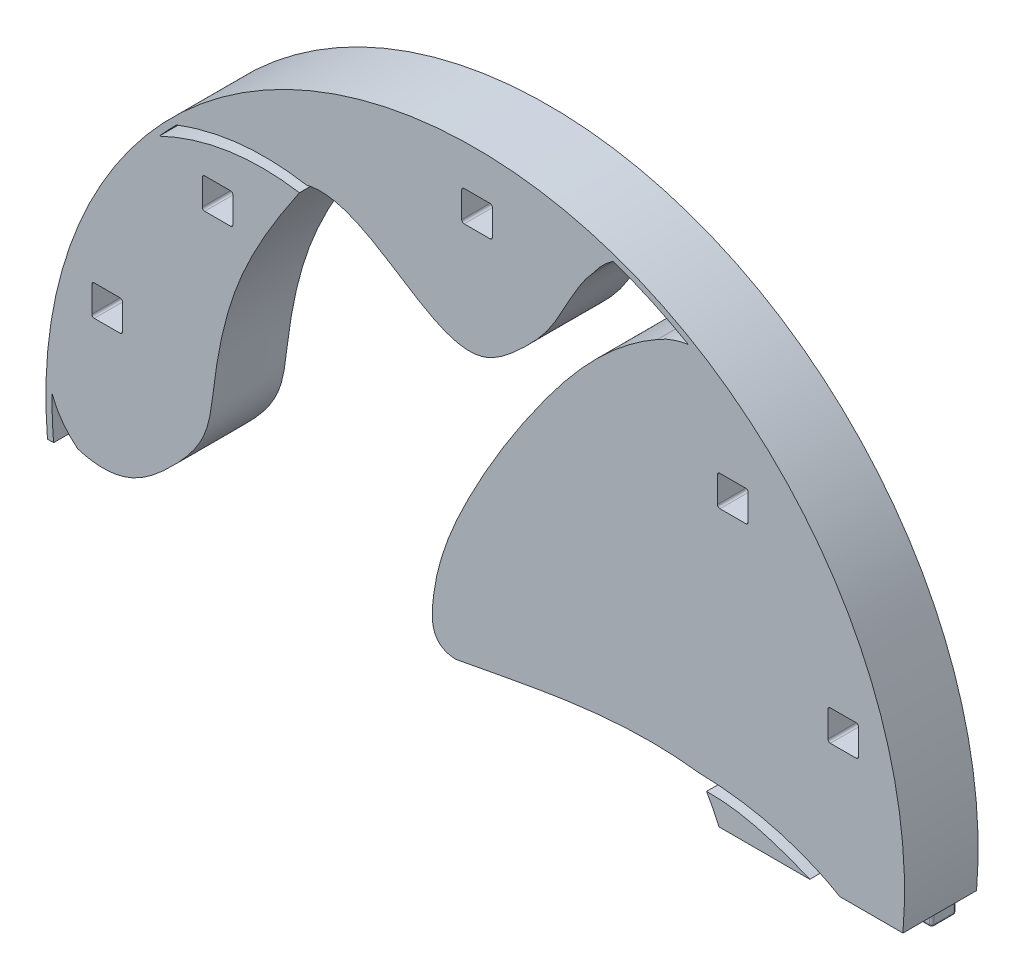
SolidWorks part; units mm, degrees
ref_plane "Front Plane" through (0, 0, 0) normal (0, 0, 1) x (1, 0, 0)
ref_plane "Top Plane" through (0, 0, 0) normal (0, 1, 0) x (1, 0, 0)
ref_plane "Right Plane" through (0, 0, 0) normal (1, 0, 0) x (0, 0, -1)
sketch "Sketch1" plane through (0, 0, 0) normal (0, 0, 1) x (1, 0, 0)
  line L0 (-471.0205, -57.4121) -> (528.9795, -57.4121) construction
sketch "Sketch2" plane through (0, 0, 0) normal (0, 0, 1) x (1, 0, 0)
  circle A0 centre (0, 0) radius 88.9
  arc A1 (-82.3152, -6.2211) -> (-81.0762, -15.5293) centre (0, 0) ccw
  arc A2 (37.7353, 73.4204) -> (24.5391, 78.8184) centre (0, 0) ccw
  arc A3 (49.8048, -65.833) -> (57.4511, -59.278) centre (0, 0) ccw
  spline S0 degree 3 poles (24.5391, 78.8184) (20.4556, 74.4117) (17.565, 65.825) (9.5129, 57.4487) (-6.2643, 43.842) (-22.0344, 67.8815) (-34.9463, 64.7741) knots 0 0 0 0 0.241589 0.34509 0.475626 1 1 1 1
  spline S1 degree 3 poles (-34.9463, 64.7741) (-40.5341, 56.6548) (-49.8264, 42.328) (-53.8975, 22.9229) (-55.1221, 8.6973) (-64.9776, -2.4901) (-73.6276, -8.8721) (-82.3152, -6.2211) knots 0 0 0 0 0.323422 0.539679 0.642017 0.776512 1 1 1 1
  spline S2 degree 3 poles (-81.0762, -15.5293) (-73.907, -10.3296) (-59.0461, -8.1934) (-41.1188, -7.6218) (-29.401, -11.3021) (-16.4021, -22.1309) (-22.5345, -39.5971) (-25.1747, -47.2363) knots 0 0 0 0 0.276571 0.483746 0.575309 0.672728 1 1 1 1
  spline S3 degree 2 poles (-25.1747, -47.2363) (-27.7826, -55.6887) (-25.2554, -64.2761) knots 0 0 0 1 1 1
  spline S4 degree 3 poles (-25.2554, -64.2761) (-19.569, -66.3264) (-8.1919, -67.1791) (6.6981, -62.4525) (13.7011, -53.6565) (20.9918, -49.375) (29.1491, -47.7149) (41.3216, -51.6056) (49.1187, -58.0567) (49.8048, -65.833) knots 0 0 0 0 0.203689 0.383929 0.501194 0.577509 0.667833 0.774874 1 1 1 1
  spline S5 degree 3 poles (57.4511, -59.278) (56.7569, -39.6924) (57.9372, -17.2532) (46.2956, 0) knots 0 0 0 0 1 1 1 1
  spline S6 degree 3 poles (46.2956, 0) (29.3524, 2.1608) (12.4769, -1.83) (-4.097, -4.8387) knots 0 0 0 0 1 1 1 1
  spline S7 degree 3 poles (-4.097, -4.8387) (-9.0033, -4.5386) (-9.1745, 2.8276) (-6.8237, 13.9795) (0.4609, 29.7843) (13.9721, 51.5725) (27.3945, 67.5356) (37.7353, 73.4204) knots 0 0 0 0 0.104628 0.200083 0.362714 0.636377 1 1 1 1
  dimension "D1" = 177.8
  dimension "D2" = 165.1
extrude "Boss-Extrude1" add sketch "Sketch2" along normal mid plane 15.24
ref_plane "Plane1" through (0, -7.62, 0) normal (0, 1, 0) x (1, 0, 0)
sketch "Sketch3" plane through (0, 0, 7.62) normal (0, 0, 1) x (1, 0, 0)
  arc A0 (45.0312, -76.6512) -> (59.2971, -66.2349) centre (0, 0) ccw
  circle A1 centre (0, 0) radius 88.9
  arc A2 (-88.6825, 6.2145) -> (-86.675, -19.7649) centre (0, 0) ccw
  arc A3 (46.2956, 75.8942) -> (29.9098, 83.7175) centre (0, 0) ccw
  arc A5 (49.8048, -65.833) -> (57.4511, -59.278) centre (0, 0) ccw
  arc A6 (-82.3152, -6.2211) -> (-81.0762, -15.5293) centre (0, 0) ccw
  arc A7 (37.7353, 73.4204) -> (24.5391, 78.8184) centre (0, 0) ccw
  arc A8 (49.8048, -65.833) -> (57.4511, -59.278) centre (0, 0) ccw
  arc A9 (-82.3152, -6.2211) -> (-81.0762, -15.5293) centre (0, 0) ccw
  arc A10 (37.7353, 73.4204) -> (24.5391, 78.8184) centre (0, 0) ccw
  parabola Q1 (-25.1747, -47.2363) -> (-25.2554, -64.2761) focus (-12.3697, -55.4847) apex (-26.4894, -55.1133)
  spline S0 degree 2 poles (24.5391, 78.8184) (26.688, 81.9029) (29.9098, 83.7175) knots 0 0 0 1 1 1
  spline S1 degree 2 poles (37.7353, 73.4204) (41.6923, 75.7816) (46.2956, 75.8942) knots 0 0 0 1 1 1
  spline S2 degree 2 poles (49.8048, -65.833) (50.2908, -72.1824) (45.0312, -76.6512) knots 0 0 0 1 1 1
  spline S3 degree 2 poles (57.4511, -59.278) (56.5901, -63.2228) (59.2971, -66.2349) knots 0 0 0 1 1 1
  spline S4 degree 2 poles (-82.3152, -6.2211) (-88.132, -1.4992) (-88.6825, 6.2145) knots 0 0 0 1 1 1
  spline S5 degree 2 poles (-81.0762, -15.5293) (-84.1856, -17.2384) (-86.675, -19.7649) knots 0 0 0 1 1 1
  spline S7 degree 3 poles (797.4031, 593.1493) (0.2989, -46.9604) (-12.291, -11.9571) (-6.8237, 13.9795) (0.4609, 29.7843) (48.148, 106.6846) (139.4225, 154.8359) (772.5047, -604.8924) knots -0.480865 -0.480865 -0.480865 -0.480865 0.104628 0.200083 0.362714 0.636377 3.023358 3.023358 3.023358 3.023358 only from (-4.097, -4.8387) to (37.7353, 73.4204)
  spline S8 degree 3 poles (252.9136, -978.4205) (116.1017, 1038.4288) (-125.7429, -1046.9057) (-203.2003, 975.1295) knots -4.374054 -4.374054 -4.374054 -4.374054 6.105359 6.105359 6.105359 6.105359 only from (46.2956, 0) to (-4.097, -4.8387)
  spline S9 degree 3 poles (990.0767, 301.5646) (-883.5718, -676.2898) (1013.4306, 526.4735) (-922.0419, -249.5528) knots -3.853706 -3.853706 -3.853706 -3.853706 4.174069 4.174069 4.174069 4.174069 only from (57.4511, -59.278) to (46.2956, 0)
  spline S10 degree 3 poles (287.5037, 885.5524) (-143.4767, 77.5467) (-70.7404, -87.034) (6.6981, -62.4525) (13.7011, -53.6565) (20.9918, -49.375) (29.1491, -47.7149) (73.6514, -61.9392) (81.5637, -140.3542) (-751.2392, -664.4206) knots -2.105379 -2.105379 -2.105379 -2.105379 0.203689 0.383929 0.501194 0.577509 0.667833 0.774874 2.12212 2.12212 2.12212 2.12212 only from (-25.2554, -64.2761) to (49.8048, -65.833)
  spline S11 degree 3 poles (118.7702, -995.3507) (-163.8661, -39.4174) (-105.7067, -9.6811) (-41.1188, -7.6218) (-29.401, -11.3021) (14.3806, -47.7745) (-197.2699, -211.0705) (662.1001, 679.1083) knots -1.497399 -1.497399 -1.497399 -1.497399 0.276571 0.483746 0.575309 0.672728 2.222535 2.222535 2.222535 2.222535 only from (-81.0762, -15.5293) to (-25.1747, -47.2363)
  spline S12 degree 3 poles (-1006.572, 301.2797) (188.103, 148.9815) (-33.2102, 121.5314) (-53.8975, 22.9229) (-55.1221, 8.6973) (-85.5018, -25.7879) (-127.0209, -26.4291) (-604.6871, 846.4702) knots -2.62044 -2.62044 -2.62044 -2.62044 0.323422 0.539679 0.642017 0.776512 1.958619 1.958619 1.958619 1.958619 only from (-34.9463, 64.7741) to (-82.3152, -6.2211)
  spline S13 degree 3 poles (862.9419, -466.2311) (-1.0647, 177.7851) (40.0673, 89.2334) (9.5129, 57.4487) (-32.0652, 21.5906) (-89.4617, 287.288) (-116.9144, -931.8483) knots -1.329179 -1.329179 -1.329179 -1.329179 0.241589 0.34509 0.475626 2.240257 2.240257 2.240257 2.240257 only from (24.5391, 78.8184) to (-34.9463, 64.7741)
  dimension "D1" = 0
  dimension "D2" = 0
extrude "Cut-Extrude1" cut sketch "Sketch3" against normal blind 5.08
sketch "Sketch4" plane through (0, 0, 7.62) normal (0, 0, 1) x (1, 0, 0)
  line L0 (-34.9463, 64.7741) -> (-35.0973, 62.4446)
  arc A0 (-64.8446, 60.8144) -> (-68.4378, 56.7404) centre (0, 0) ccw
  circle A1 centre (0, 0) radius 88.9
  arc A2 (0.6318, -88.8978) -> (4.2385, -88.7989) centre (0, 0) ccw
  arc A3 (86.0164, -22.4585) -> (86.9207, -18.6546) centre (0, 0) ccw
  arc A5 (49.8048, -65.833) -> (57.4511, -59.278) centre (0, 0) ccw
  arc A6 (-82.3152, -6.2211) -> (-81.0762, -15.5293) centre (0, 0) ccw
  arc A7 (37.7353, 73.4204) -> (24.5391, 78.8184) centre (0, 0) ccw
  parabola Q1 (-25.1747, -47.2363) -> (-25.2554, -64.2761) focus (-12.3697, -55.4847) apex (-26.4894, -55.1133)
  spline S0 degree 2 poles (-34.9463, 64.7741) (-50.3518, 67.3824) (-64.8446, 60.8144) knots 0 0 0 1 1 1
  spline S1 degree 2 poles (-35.0973, 62.4446) (-52.4249, 65.6078) (-68.4378, 56.7404) knots 0 0 0 1 1 1
  spline S2 degree 3 poles (46.2956, 0) (53.1383, -0.1215) (68.5609, -2.5532) (82.3308, -11.0602) (86.9207, -18.6546) knots 0 0 0 0 0.442007 1 1 1 1
  spline S3 degree 3 poles (47.9006, -2.5461) (54.1052, -2.3836) (68.546, -6.4117) (82.2788, -13.6612) (86.0164, -22.4585) knots 0 0 0 0 0.409341 1 1 1 1
  spline S4 degree 3 poles (-25.2554, -64.2761) (-21.1278, -75.8582) (-10.4674, -84.3936) (0.6318, -88.8978) knots 0 0 0 0 1 1 1 1
  spline S5 degree 3 poles (-22.4522, -65.1518) (-17.4352, -76.2865) (-6.0163, -83.0979) (4.2385, -88.7989) knots 0 0 0 0 1 1 1 1
  spline S7 degree 3 poles (797.4031, 593.1493) (0.2989, -46.9604) (-12.291, -11.9571) (-6.8237, 13.9795) (0.4609, 29.7843) (48.148, 106.6846) (139.4225, 154.8359) (772.5047, -604.8924) knots -0.480865 -0.480865 -0.480865 -0.480865 0.104628 0.200083 0.362714 0.636377 3.023358 3.023358 3.023358 3.023358 only from (-4.097, -4.8387) to (37.7353, 73.4204)
  spline S8 degree 3 poles (252.9136, -978.4205) (116.1017, 1038.4288) (-125.7429, -1046.9057) (-203.2003, 975.1295) knots -4.374054 -4.374054 -4.374054 -4.374054 6.105359 6.105359 6.105359 6.105359 only from (46.2956, 0) to (-4.097, -4.8387)
  spline S9 degree 3 poles (2750.4497, 1250.492) (-2664.0011, -1715.2033) (2817.268, 1518.6416) (-2752.7289, -1054.4103) knots -5.547082 -5.547082 -5.547082 -5.547082 5.883178 5.883178 5.883178 5.883178 only from (57.4511, -59.278) to (46.2956, 0)
  spline S10 degree 3 poles (1330.581, 2591.3174) (-209.0004, 264.8137) (-104.1775, -97.6481) (6.6981, -62.4525) (13.7011, -53.6565) (20.9918, -49.375) (29.1491, -47.7149) (91.1887, -67.5447) (82.2329, -217.3865) (-2469.3122, -1687.681) knots -3.230872 -3.230872 -3.230872 -3.230872 0.203689 0.383929 0.501194 0.577509 0.667833 0.774874 2.730813 2.730813 2.730813 2.730813 only from (-25.2554, -64.2761) to (49.8048, -65.833)
  spline S11 degree 3 poles (118.7702, -995.3507) (-163.8661, -39.4174) (-105.7067, -9.6811) (-41.1188, -7.6218) (-29.401, -11.3021) (14.3806, -47.7745) (-197.2699, -211.0705) (662.1001, 679.1083) knots -1.497399 -1.497399 -1.497399 -1.497399 0.276571 0.483746 0.575309 0.672728 2.222535 2.222535 2.222535 2.222535 only from (-81.0762, -15.5293) to (-25.1747, -47.2363)
  spline S12 degree 3 poles (-2993.0961, 532.3769) (364.9707, 159.8233) (-26.2899, 154.5178) (-53.8975, 22.9229) (-55.1221, 8.6973) (-96.7925, -38.6043) (-162.4194, -21.9121) (-1545.0332, 2611.4959) knots -3.711795 -3.711795 -3.711795 -3.711795 0.323422 0.539679 0.642017 0.776512 2.485967 2.485967 2.485967 2.485967 only from (-34.9463, 64.7741) to (-82.3152, -6.2211)
  spline S13 degree 3 poles (862.9419, -466.2311) (-1.0647, 177.7851) (40.0673, 89.2334) (9.5129, 57.4487) (-32.0652, 21.5906) (-89.4617, 287.288) (-116.9144, -931.8483) knots -1.329179 -1.329179 -1.329179 -1.329179 0.241589 0.34509 0.475626 2.240257 2.240257 2.240257 2.240257 only from (24.5391, 78.8184) to (-34.9463, 64.7741)
  spline S16 degree 3 poles (47.9006, -2.5461) (47.3947, -1.6858) (46.8602, -0.8368) (46.2956, 0) knots 0.951499 0.951499 0.951499 0.951499 1 1 1 1
  spline S17 degree 3 poles (-25.2554, -64.2761) (-24.3298, -64.6099) (-23.3949, -64.9013) (-22.4522, -65.1518) knots 0 0 0 0 0.033156 0.033156 0.033156 0.033156
  spline S19 degree 3 poles (-34.9463, 64.7741) (-35.4279, 64.0742) (-35.9094, 63.371) (-36.3894, 62.664) knots 0 0 0 0 0.027876 0.027876 0.027876 0.027876
  dimension "D1" = 0
  dimension "D2" = 0
extrude "Cut-Extrude2" cut sketch "Sketch4" against normal blind 5.08 contours S16 S3 A3 S2 | S17 S4 A2 S5 | S0 A0 S1 L0
sketch "Sketch5" plane through (0, -7.62, 0) normal (0, 1, 0) x (1, 0, 0)
  line L1 (-223.9278, 48.3173) -> (223.9278, 48.3173)
  line L2 (-223.9278, 48.3173) -> (-223.9278, -48.3173)
  line L3 (-223.9278, -48.3173) -> (223.9278, -48.3173)
  line L4 (223.9278, 48.3173) -> (223.9278, -48.3173)
  line L5 (-223.9278, 48.3173) -> (223.9278, -48.3173) construction
  line L6 (-223.9278, -48.3173) -> (223.9278, 48.3173) construction
  point P0 (0, 0)
sketch "Sketch6" plane through (0, 0, 0) normal (0, 0, 1) x (1, 0, 0)
  circle A0 centre (0, 0) radius 88.9
  circle A1 centre (0, 0) radius 87.63
  dimension "D1" = 177.8
  dimension "D2" = 175.26
extrude "Boss-Extrude2" add sketch "Sketch6" along normal mid plane 15.24
extrude "Cut-Extrude3" cut sketch "Sketch5" against normal through all
sketch "Sketch7" plane through (0, -7.62, 0) normal (0, -1, 0) x (1, 0, 0)
  line L8 (-86.4012, 0) -> (-84.3692, 0)
  line L9 (-86.9092, -0.508) -> (-86.9092, -4.572)
  line L10 (-86.4012, -5.08) -> (-84.3692, -5.08)
  line L11 (-83.8612, -0.508) -> (-83.8612, -4.572)
  line L12 (-82.1976, -7.62) -> (-88.5728, -7.62) construction
  line L13 (-82.1976, -7.62) -> (-82.1976, 2.54) construction
  line L16 (0, 0) -> (0, 5.9211) construction
  line L21 (86.9092, -0.508) -> (86.9092, -4.572)
  line L22 (86.4012, -5.08) -> (84.3692, -5.08)
  line L23 (83.8612, -0.508) -> (83.8612, -4.572)
  line L24 (86.4012, 0) -> (84.3692, 0)
  arc A0 (-86.9092, -4.572) -> (-86.4012, -5.08) centre (-86.4012, -4.572) ccw
  arc A1 (-84.3692, 0) -> (-83.8612, -0.508) centre (-84.3692, -0.508) cw
  arc A2 (-84.3692, -5.08) -> (-83.8612, -4.572) centre (-84.3692, -4.572) ccw
  arc A3 (-86.4012, 0) -> (-86.9092, -0.508) centre (-86.4012, -0.508) ccw
  arc A4 (86.9092, -4.572) -> (86.4012, -5.08) centre (86.4012, -4.572) cw
  arc A5 (84.3692, -5.08) -> (83.8612, -4.572) centre (84.3692, -4.572) cw
  arc A6 (84.3692, 0) -> (83.8612, -0.508) centre (84.3692, -0.508) ccw
  arc A7 (86.4012, 0) -> (86.9092, -0.508) centre (86.4012, -0.508) cw
  point P8 (-86.9092, -5.08)
  point P16 (-85.3852, -7.62)
  point P17 (-85.3852, -5.08)
  point P20 (-82.1976, -2.54)
  point P21 (-83.8612, -2.54)
  point P24 (-83.8612, 0)
  point P27 (-83.8612, -5.08)
  point P30 (-86.9092, 0)
  dimension "D1" = 0.508
  dimension "D5" = 3.048
  dimension "D6" = 5.08
extrude "Boss-Extrude3" add sketch "Sketch7" along normal blind 3.81
fillet "Fillet1" radius 0.508 16 edges at (86.7604, -11.43, -0.1488) (86.9092, -11.43, -2.54) (86.7604, -11.43, -4.9312) (85.3852, -11.43, -5.08) (84.01, -11.43, -4.9312) (83.8612, -11.43, -2.54) (84.01, -11.43, -0.1488) (-84.01, -11.43, -0.1488) (-83.8612, -11.43, -2.54) (-84.01, -11.43, -4.9312) (-85.3852, -11.43, -5.08) (-86.7604, -11.43, -4.9312) (-86.9092, -11.43, -2.54) (-86.7604, -11.43, -0.1488) (85.3852, -11.43, 0) (-85.3852, -11.43, 0)
sketch "Sketch9" plane through (0, 0, 7.62) normal (0, 0, 1) x (1, 0, 0)
  ellipse E0 centre (0.3832, 77.3071) end of major axis (0.3832, 68.4171) minor radius 5.08
  ellipse E1 centre (-53.34, 52.7037) end of major axis (-53.34, 43.8137) minor radius 5.08
  ellipse E2 centre (-76.2, 22.0754) end of major axis (-76.2, 13.1854) minor radius 5.08
  ellipse E3 centre (53.34, 52.7037) end of major axis (53.34, 43.8137) minor radius 5.08
  ellipse E4 centre (76.2, 22.0754) end of major axis (76.2, 13.1854) minor radius 5.08
  point P32 (-76.2, 22.0754)
  point P33 (0.3832, 77.3071)
  point P34 (53.34, 52.7037)
  point P36 (-53.34, 52.7037)
  dimension "D1" = 10.16
  dimension "D2" = 17.78
  dimension "D3" = 53.34
  dimension "D4" = 53.34
  dimension "D5" = 76.2
  dimension "D6" = 76.2
sketch "Sketch10" plane through (0, 0, 7.62) normal (0, 0, 1) x (1, 0, 0)
  point P0 (-76.2, 22.0754)
  point P1 (-53.34, 52.7037)
  point P3 (0.3832, 77.3071)
  point P5 (53.34, 52.7037)
  point P7 (76.2, 22.0754)
sketch "Sketch11" plane through (0, 0, 7.62) normal (0, 0, 1) x (1, 0, 0)
  line L1 (-78.867, 25.2504) -> (-73.533, 25.2504)
  line L2 (-79.375, 24.7424) -> (-79.375, 19.4084)
  line L3 (-78.867, 18.9004) -> (-73.533, 18.9004)
  line L4 (-73.025, 24.7424) -> (-73.025, 19.4084)
  line L5 (-79.375, 25.2504) -> (-73.025, 18.9004) construction
  line L6 (-79.375, 18.9004) -> (-73.025, 25.2504) construction
  line L7 (-56.007, 55.8787) -> (-50.673, 55.8787)
  line L8 (-56.515, 55.3707) -> (-56.515, 50.0367)
  line L9 (-56.007, 49.5287) -> (-50.673, 49.5287)
  line L10 (-50.165, 55.3707) -> (-50.165, 50.0367)
  line L11 (-56.515, 55.8787) -> (-50.165, 49.5287) construction
  line L12 (-56.515, 49.5287) -> (-50.165, 55.8787) construction
  line L13 (-2.2838, 80.4821) -> (3.0502, 80.4821)
  line L14 (-2.7918, 79.9741) -> (-2.7918, 74.6401)
  line L15 (-2.2838, 74.1321) -> (3.0502, 74.1321)
  line L16 (3.5582, 79.9741) -> (3.5582, 74.6401)
  line L17 (-2.7918, 80.4821) -> (3.5582, 74.1321) construction
  line L18 (-2.7918, 74.1321) -> (3.5582, 80.4821) construction
  line L19 (50.673, 55.8787) -> (56.007, 55.8787)
  line L20 (50.165, 55.3707) -> (50.165, 50.0367)
  line L21 (50.673, 49.5287) -> (56.007, 49.5287)
  line L22 (56.515, 55.3707) -> (56.515, 50.0367)
  line L23 (50.165, 55.8787) -> (56.515, 49.5287) construction
  line L24 (50.165, 49.5287) -> (56.515, 55.8787) construction
  line L25 (73.533, 25.2504) -> (78.867, 25.2504)
  line L26 (73.025, 24.7424) -> (73.025, 19.4084)
  line L27 (73.533, 18.9004) -> (78.867, 18.9004)
  line L28 (79.375, 24.7424) -> (79.375, 19.4084)
  line L29 (73.025, 25.2504) -> (79.375, 18.9004) construction
  line L30 (73.025, 18.9004) -> (79.375, 25.2504) construction
  arc A0 (-79.375, 19.4084) -> (-78.867, 18.9004) centre (-78.867, 19.4084) ccw
  arc A1 (-73.533, 18.9004) -> (-73.025, 19.4084) centre (-73.533, 19.4084) ccw
  arc A2 (-73.533, 25.2504) -> (-73.025, 24.7424) centre (-73.533, 24.7424) cw
  arc A3 (-78.867, 25.2504) -> (-79.375, 24.7424) centre (-78.867, 24.7424) ccw
  arc A4 (-56.515, 50.0367) -> (-56.007, 49.5287) centre (-56.007, 50.0367) ccw
  arc A5 (-50.673, 49.5287) -> (-50.165, 50.0367) centre (-50.673, 50.0367) ccw
  arc A6 (-50.673, 55.8787) -> (-50.165, 55.3707) centre (-50.673, 55.3707) cw
  arc A7 (-56.007, 55.8787) -> (-56.515, 55.3707) centre (-56.007, 55.3707) ccw
  arc A8 (3.0502, 80.4821) -> (3.5582, 79.9741) centre (3.0502, 79.9741) cw
  arc A9 (3.0502, 74.1321) -> (3.5582, 74.6401) centre (3.0502, 74.6401) ccw
  arc A10 (-2.7918, 74.6401) -> (-2.2838, 74.1321) centre (-2.2838, 74.6401) ccw
  arc A11 (-2.2838, 80.4821) -> (-2.7918, 79.9741) centre (-2.2838, 79.9741) ccw
  arc A12 (56.007, 49.5287) -> (56.515, 50.0367) centre (56.007, 50.0367) ccw
  arc A13 (56.007, 55.8787) -> (56.515, 55.3707) centre (56.007, 55.3707) cw
  arc A14 (50.673, 49.5287) -> (50.165, 50.0367) centre (50.673, 50.0367) cw
  arc A15 (50.673, 55.8787) -> (50.165, 55.3707) centre (50.673, 55.3707) ccw
  arc A16 (78.867, 25.2504) -> (79.375, 24.7424) centre (78.867, 24.7424) cw
  arc A17 (78.867, 18.9004) -> (79.375, 19.4084) centre (78.867, 19.4084) ccw
  arc A18 (73.025, 19.4084) -> (73.533, 18.9004) centre (73.533, 19.4084) ccw
  arc A19 (73.533, 25.2504) -> (73.025, 24.7424) centre (73.533, 24.7424) ccw
  point P0 (-76.2, 22.0754)
  point P18 (-53.34, 52.7037)
  point P36 (0.3832, 77.3071)
  point P54 (53.34, 52.7037)
  point P72 (76.2, 22.0754)
  dimension "D3" = 0.508
  dimension "D6" = 0.508
  dimension "D9" = 0.508
  dimension "D12" = 0.508
  dimension "D15" = 0.508
  dimension "D1" = 6.35
  dimension "D2" = 6.35
  dimension "D4" = 6.35
  dimension "D5" = 6.35
  dimension "D7" = 6.35
  dimension "D8" = 6.35
  dimension "D10" = 6.35
  dimension "D11" = 6.35
  dimension "D13" = 6.35
  dimension "D14" = 6.35
extrude "Cut-Extrude4" cut sketch "Sketch11" against normal blind 6.604
sketch "Sketch12" plane through (0, 0, 7.62) normal (0, 0, 1) x (1, 0, 0)
  ellipse E0 centre (-53.34, 52.7037) end of major axis (-53.34, 43.8137) minor radius 6.35
  dimension "D1" = 12.7
  dimension "D2" = 17.78
